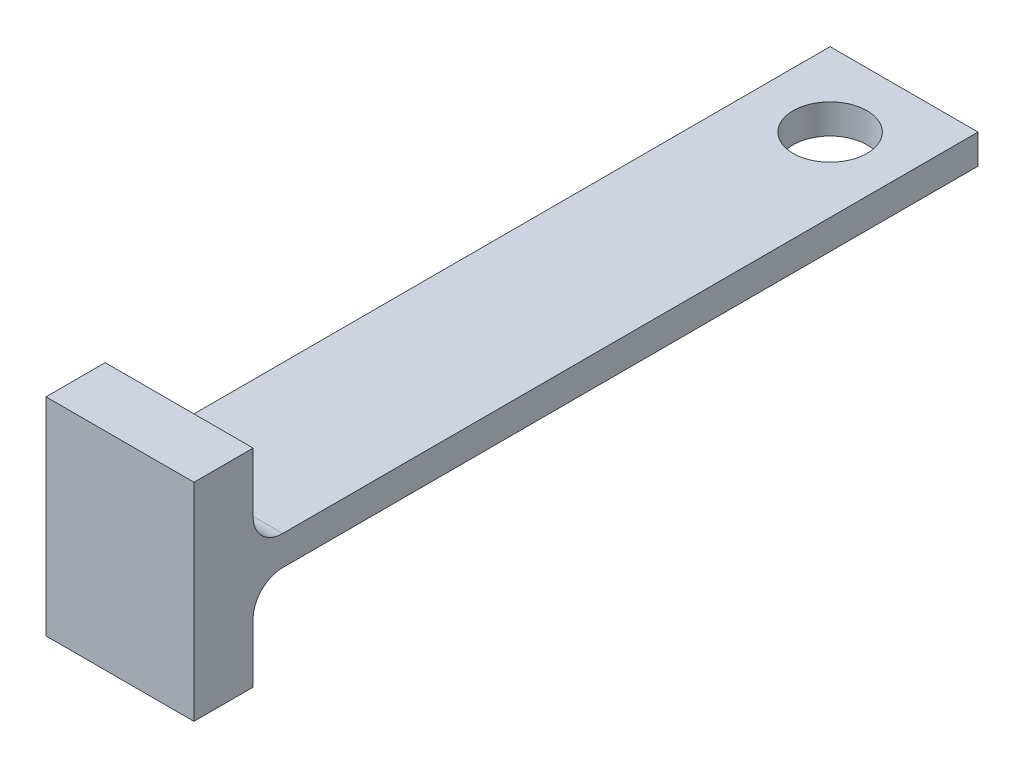
SolidWorks part; units mm, degrees
ref_plane "Front Plane" through (0, 0, 0) normal (0, 0, 1) x (1, 0, 0)
ref_plane "Top Plane" through (0, 0, 0) normal (0, 1, 0) x (1, 0, 0)
ref_plane "Right Plane" through (0, 0, 0) normal (1, 0, 0) x (0, 0, -1)
sketch "Sketch1" plane through (0, 0, 0) normal (0, 1, 0) x (1, 0, 0)
  line L1 (0, 0) -> (-50, 0)
  line L2 (0, 0) -> (0, 265)
  line L3 (0, 265) -> (-50, 265)
  line L4 (-50, 0) -> (-50, 265)
  circle A0 centre (-25, 240) radius 12.5
  dimension "D5" = 25
  dimension "D1" = 265
  dimension "D2" = 50
  dimension "D3" = 25
  dimension "D4" = 25
extrude "Boss-Extrude1" add sketch "Sketch1" along normal blind 10
sketch "Sketch2" plane through (0, 10, 0) normal (0, 1, 0) x (1, 0, 0)
  line L0 (-50, 265) -> (-50, 0) construction
  line L1 (0, 0) -> (-50, 0)
  line L2 (0, 0) -> (0, 20)
  line L3 (0, 20) -> (-50, 20)
  line L4 (-50, 0) -> (-50, 20)
  dimension "D1" = 20
extrude "Boss-Extrude2" add sketch "Sketch2" along normal blind 30
sketch "Sketch3" plane through (0, 0, 0) normal (0, -1, 0) x (1, 0, 0)
  line L0 (-50, -265) -> (-50, 0) construction
  line L1 (0, 0) -> (-50, 0)
  line L2 (0, 0) -> (0, -20)
  line L3 (0, -20) -> (-50, -20)
  line L4 (-50, 0) -> (-50, -20)
  dimension "D1" = 20
extrude "Boss-Extrude3" add sketch "Sketch3" along normal blind 30
fillet "Fillet1" radius 10 2 edges
